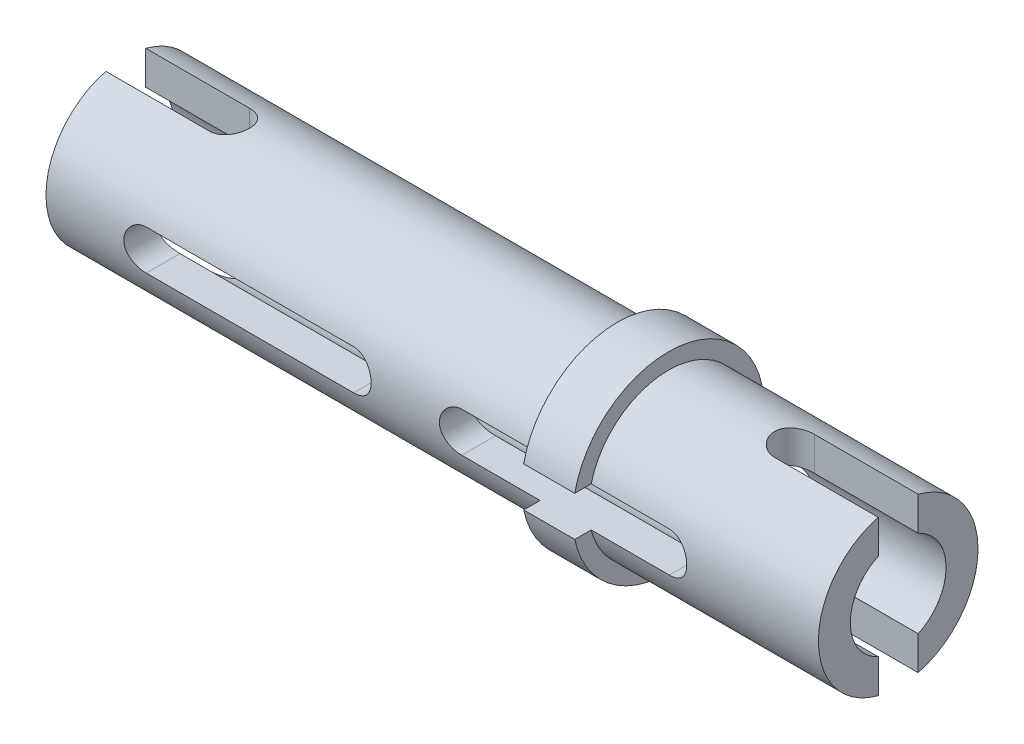
SolidWorks part; units mm, degrees
other "DetailItem1"
other "DetailItem2"
other "DetailItem3"
other "DetailItem4"
other "DetailItem5"
other "DetailItem6"
other "DetailItem7"
other "DetailItem8"
other "DetailItem9"
other "DetailItem10"
other "DetailItem11"
other "DetailItem12"
ref_plane "Front Plane" through (0, 0, 0) normal (0, 0, 1) x (1, 0, 0)
ref_plane "Top Plane" through (0, 0, 0) normal (0, 1, 0) x (1, 0, 0)
ref_plane "Right Plane" through (0, 0, 0) normal (1, 0, 0) x (0, 0, -1)
sketch "Sketch1" plane through (0, 0, 0) normal (1, 0, 0) x (0, 0, -1)
  circle A0 centre (0, 0) radius 3
  dimension "D1" = 6
extrude "Boss-Extrude1" add sketch "Sketch1" along normal mid plane 1.6
sketch "Sketch2" plane through (0.8, 0, 0) normal (1, 0, 0) x (0, 0, -1)
  circle A0 centre (0, 0) radius 2.5
  dimension "D1" = 5
extrude "Boss-Extrude2" add sketch "Sketch2" along normal offset from surface 8 and the other way blind 17 up to plane "Right Plane"
sketch "Sketch3" plane through (0, 0, 0) normal (0, 0, 1) x (1, 0, 0)
  line L0 (-3.25, 0) -> (3.25, 0) construction
  line L1 (-3.25, 0.625) -> (3.25, 0.625)
  line L2 (-3.25, -0.625) -> (3.25, -0.625)
  line L3 (-13.139, 0) -> (-6.639, 0) construction
  line L4 (-13.139, 0.625) -> (-6.639, 0.625)
  line L5 (-13.139, -0.625) -> (-6.639, -0.625)
  arc A0 (-3.25, 0.625) -> (-3.25, -0.625) centre (-3.25, 0) ccw
  arc A1 (3.25, -0.625) -> (3.25, 0.625) centre (3.25, 0) ccw
  arc A2 (-13.139, 0.625) -> (-13.139, -0.625) centre (-13.139, 0) ccw
  arc A3 (-6.639, -0.625) -> (-6.639, 0.625) centre (-6.639, 0) ccw
  point P2 (0, 0)
  point P9 (-9.889, 0)
  dimension "D1" = 6.5
  dimension "D2" = 1.25
  dimension "D3" = 6.5
  dimension "D4" = 1.25
extrude "Cut-Extrude1" cut sketch "Sketch3" against normal through all and the other way through all
sketch "Sketch4" plane through (8, 0, 0) normal (1, 0, 0) x (0, 0, -1)
  circle A0 centre (0, 0) radius 1.5
  dimension "D1" = 3
extrude "Cut-Extrude2" cut sketch "Sketch4" against normal through all
sketch "Sketch5" plane through (0, 0, 0) normal (0, 1, 0) x (1, 0, 0)
  line L0 (-19.45, 0) -> (-12.95, 0) construction
  line L1 (-16.2, 2.5) -> (-16.2, -2.5) construction
  line L2 (-19.45, 0.625) -> (-12.95, 0.625)
  line L3 (-19.45, -0.625) -> (-12.95, -0.625)
  line L4 (11.25, 0) -> (4.75, 0) construction
  line L5 (8, -2.5) -> (8, 2.5) construction
  line L6 (11.25, -0.625) -> (4.75, -0.625)
  line L7 (11.25, 0.625) -> (4.75, 0.625)
  arc A0 (-19.45, 0.625) -> (-19.45, -0.625) centre (-19.45, 0) ccw
  arc A1 (-12.95, -0.625) -> (-12.95, 0.625) centre (-12.95, 0) ccw
  arc A2 (11.25, -0.625) -> (11.25, 0.625) centre (11.25, 0) ccw
  arc A3 (4.75, 0.625) -> (4.75, -0.625) centre (4.75, 0) ccw
  point P5 (-16.2, 0)
  point P11 (8, 0)
  dimension "D1" = 6.5
  dimension "D2" = 6.5
  dimension "D3" = 1.25
  dimension "D4" = 1.25
extrude "Cut-Extrude3" cut sketch "Sketch5" against normal through all and the other way through all
